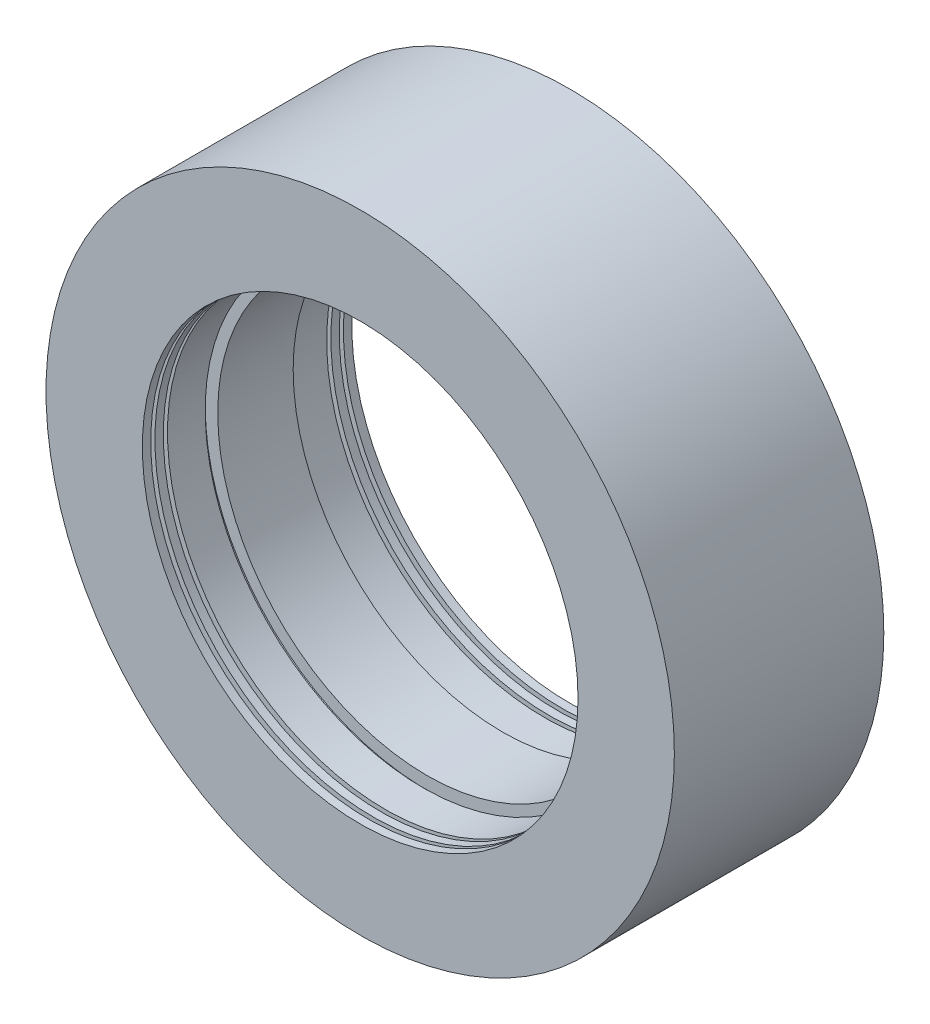
SolidWorks part; units mm, degrees
ref_plane "Front Plane" through (0, 0, 0) normal (0, 0, 1) x (1, 0, 0)
ref_plane "Top Plane" through (0, 0, 0) normal (0, 1, 0) x (1, 0, 0)
ref_plane "Right Plane" through (0, 0, 0) normal (1, 0, 0) x (0, 0, -1)
sketch "Sketch1" plane through (0, 0, 0) normal (1, 0, 0) x (0, 0, -1)
  line L28 (-142.7496, 73.5029) -> (-92.7496, 73.5029)
  line L29 (-142.7496, 73.5029) -> (-142.7496, 50.5029)
  line L30 (-92.7496, 73.5029) -> (-92.7496, 50.5029)
  line L31 (-142.7496, 50.5029) -> (-140.7496, 50.5029)
  line L32 (-140.7496, 50.5029) -> (-140.7496, 52.5029)
  line L33 (-140.7496, 52.5029) -> (-139.7496, 52.5029)
  line L34 (-139.7496, 52.5029) -> (-139.7496, 50.5029)
  line L35 (-139.7496, 50.5029) -> (-137.7496, 50.5029)
  line L36 (-137.7496, 50.5029) -> (-137.7496, 52.5029)
  line L37 (-137.7496, 52.5029) -> (-136.7496, 52.5029)
  line L38 (-136.7496, 52.5029) -> (-136.7496, 50.5029)
  line L39 (-136.7496, 50.5029) -> (-127.7496, 50.5029)
  line L40 (-127.7496, 50.5029) -> (-127.7496, 51.5029)
  line L41 (-127.7496, 51.5029) -> (-126.7496, 51.5029)
  line L42 (-126.7496, 51.5029) -> (-126.7496, 48.5029)
  line L43 (-92.7496, 50.5029) -> (-94.7496, 50.5029)
  line L44 (-94.7496, 50.5029) -> (-94.7496, 52.5029)
  line L45 (-94.7496, 52.5029) -> (-95.7496, 52.5029)
  line L46 (-95.7496, 52.5029) -> (-95.7496, 50.5029)
  line L47 (-95.7496, 50.5029) -> (-97.7496, 50.5029)
  line L48 (-97.7496, 50.5029) -> (-97.7496, 52.5029)
  line L49 (-97.7496, 52.5029) -> (-98.7496, 52.5029)
  line L50 (-98.7496, 52.5029) -> (-98.7496, 50.5029)
  line L51 (-98.7496, 50.5029) -> (-107.7496, 50.5029)
  line L52 (-107.7496, 50.5029) -> (-107.7496, 51.5029)
  line L53 (-107.7496, 51.5029) -> (-108.7496, 51.5029)
  line L54 (-108.7496, 51.5029) -> (-108.7496, 48.5029)
  line L56 (-126.7496, 48.5029) -> (-108.7496, 48.5029)
  line L57 (-168.1922, -1.4971) -> (-63.1503, -1.4971) construction
  dimension "D1" = 50
  dimension "D2" = 2
  dimension "D3" = 2
  dimension "D4" = 1
  dimension "D5" = 1
  dimension "D6" = 9
  dimension "D7" = 1
  dimension "D8" = 1
  dimension "D9" = 3
  dimension "D10" = 2
  dimension "D11" = 2
  dimension "D12" = 1
  dimension "D13" = 2
  dimension "D14" = 1
  dimension "D15" = 9
  dimension "D16" = 1
  dimension "D17" = 23
  dimension "D18" = 52
revolve "Revolve1" add sketch "Sketch1" angle 360 about L57
